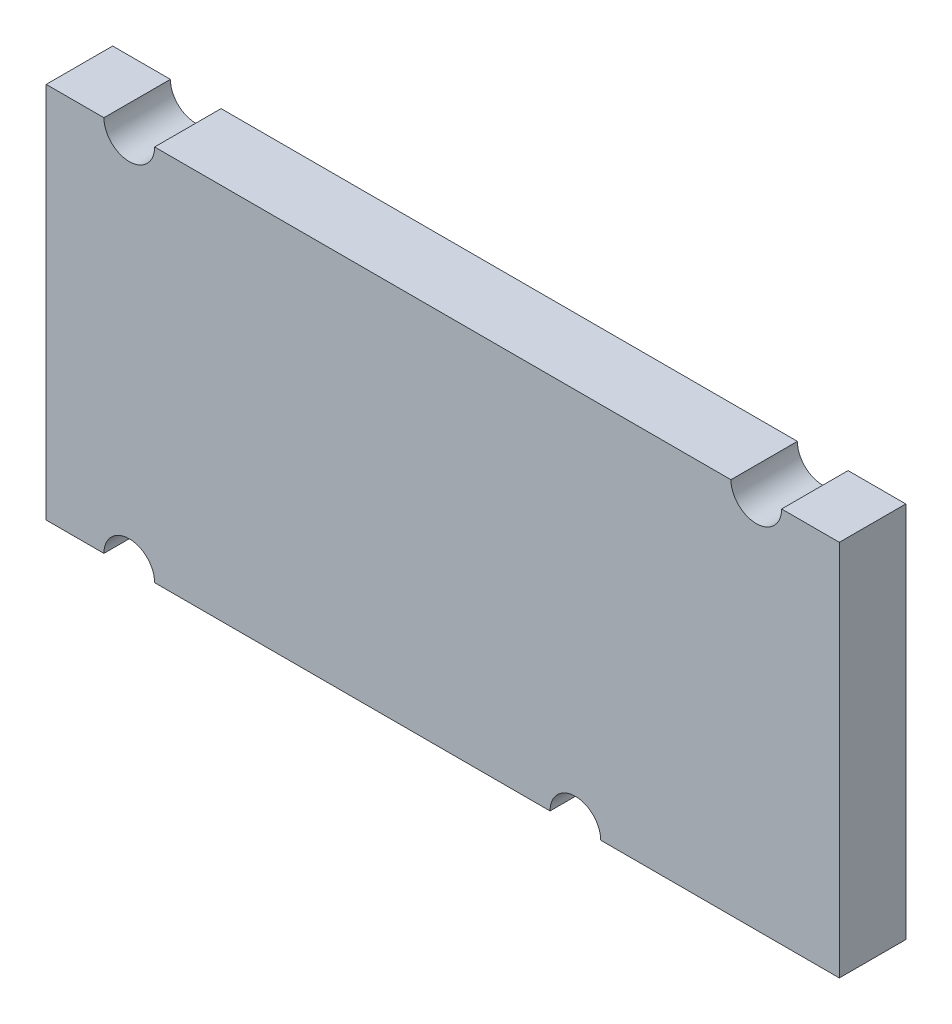
SolidWorks part; units mm, degrees
ref_plane "前视基准面" through (0, 0, 0) normal (0, 0, 1) x (1, 0, 0)
ref_plane "上视基准面" through (0, 0, 0) normal (0, 1, 0) x (1, 0, 0)
ref_plane "右视基准面" through (0, 0, 0) normal (1, 0, 0) x (0, 0, -1)
other "Configuration Table"
sketch "草图1" plane through (0, 0, 0) normal (0, 0, 1) x (1, 0, 0)
  line L0 (27.6219, -11.5) -> (27.6219, 12.73) construction
  line L1 (-20.1147, 11.355) -> (27.6219, 11.355)
  line L2 (-20.1147, 11.355) -> (-20.1147, -11.355)
  line L3 (-20.1147, -11.355) -> (27.6219, -11.355)
  line L4 (27.6219, 11.355) -> (27.6219, -11.355)
  line L5 (-20.1147, 12.73) -> (-20.1147, -12.73) construction
  arc A0 (-13.7397, -11.355) -> (-16.4897, -11.355) centre (-15.1147, -11.355) ccw construction
  arc A1 (-16.4897, 11.355) -> (-13.7397, 11.355) centre (-15.1147, 11.355) ccw construction
  arc A2 (21.2469, 11.355) -> (23.9969, 11.355) centre (22.6219, 11.355) ccw construction
  arc A3 (13.1103, -11.355) -> (10.3603, -11.355) centre (11.7353, -11.355) ccw construction
  circle A25 centre (-15.1147, 11.355) radius 1.525
  circle A28 centre (22.6219, 11.355) radius 1.525
  circle A31 centre (-15.1147, -11.355) radius 1.525
  circle A34 centre (11.7353, -11.355) radius 1.525
  point P7 (-16.6878, -11.4652)
  point P10 (-15.1147, -11.3321)
  dimension "D1" = 0.15
extrude "凸台-拉伸1" add sketch "草图1" along normal blind 4 contours A34 L3 L4 L1 A28 A25 L2 A31
